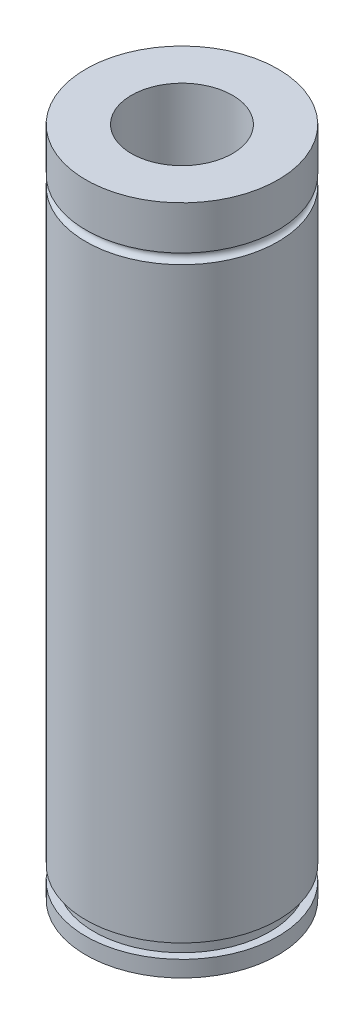
SolidWorks part; units mm, degrees
ref_plane "Front Plane" through (0, 0, 0) normal (0, 0, 1) x (1, 0, 0)
ref_plane "Top Plane" through (0, 0, 0) normal (0, 1, 0) x (1, 0, 0)
ref_plane "Right Plane" through (0, 0, 0) normal (1, 0, 0) x (0, 0, -1)
sketch "Sketch1" plane through (0, 0, 0) normal (0, 0, 1) x (1, 0, 0)
  line L0 (0, 0) -> (47.5, 0)
  line L1 (47.5, 0) -> (47.5, 8)
  line L2 (47.5, 8) -> (43.5, 8)
  line L3 (43.5, 8) -> (43.5, 15)
  line L4 (43.5, 15) -> (47.5, 15)
  line L5 (47.5, 15) -> (47.5, 305.5)
  line L6 (47.5, 332) -> (25, 332)
  line L7 (25, 332) -> (25, 82)
  line L8 (25, 82) -> (0, 82)
  line L9 (0, 82) -> (0, 0)
  line L10 (0, 0) -> (0, 458.8883) construction
  line L11 (47.5, 310.5) -> (47.5, 332)
  arc A0 (47.5, 310.5) -> (47.5, 305.5) centre (47.5, 308) ccw
  dimension "D9" = 2.5
  dimension "D1" = 95
  dimension "D2" = 8
  dimension "D3" = 87
  dimension "D4" = 7
  dimension "D5" = 317
  dimension "D6" = 50
  dimension "D7" = 250
  dimension "D8" = 24
revolve "Revolve1" add sketch "Sketch1" angle 360 about L10
sketch "Sketch2" plane through (0, 0, 0) normal (0, -1, 0) x (1, 0, 0)
  line L3 (21.2132, -21.2132) -> (-21.2132, -21.2132) construction
  line L4 (21.2132, -21.2132) -> (21.2132, 21.2132) construction
  line L5 (21.2132, 21.2132) -> (-21.2132, 21.2132) construction
  line L6 (-21.2132, -21.2132) -> (-21.2132, 21.2132) construction
  line L7 (21.2132, -21.2132) -> (-21.2132, 21.2132) construction
  line L8 (21.2132, 21.2132) -> (-21.2132, -21.2132) construction
  circle A0 centre (0, 0) radius 30 construction
  dimension "D1" = 60
hole_wizard "M8 Tapped Hole1" positions "3DSketch1" profile "Sketch3" tap size "M8" standard "ISO"
sketch3d "3DSketch1"
  point P0 (21.2132, 0, 21.2132)
  point P3 (-21.2132, 0, 21.2132)
  point P6 (-21.2132, 0, -21.2132)
  point P9 (21.2132, 0, -21.2132)
sketch "Sketch3" plane through (21.2132, 0, 21.2132) normal (1, 0, 0) x (0, 0, -1)
  line L0 (0, 0) -> (0, 18.7929)
  line L1 (0, 18.7929) -> (3.4, 16.75)
  line L2 (3.4, 16.75) -> (3.4, 0.625)
  line L3 (3.4, 0.625) -> (4.025, 0)
  line L5 (4.025, 0) -> (0, 0)
  line L6 (-3.4, 0.625) -> (-4.025, 0) construction
  line L10 (0, 18.7929) -> (-3.4, 16.75) construction
  line L11 (0, -6.35) -> (0, 107.95) construction
  dimension "Tap Drill Dia." = 6.8
  dimension "Tap Drill Depth" = 16.75
  dimension "Near C'Sink Dia." = 8.05
  dimension "Near C'Sink Angle" = 90
  dimension "Drill Angle" = 118
cosmetic thread "Hole Thread1" parameters "D1"=13, "D2"=8
cosmetic thread "Hole Thread2" parameters "D1"=13, "D2"=8
cosmetic thread "Hole Thread3" parameters "D1"=13, "D2"=8
cosmetic thread "Hole Thread4" parameters "D1"=13, "D2"=8
